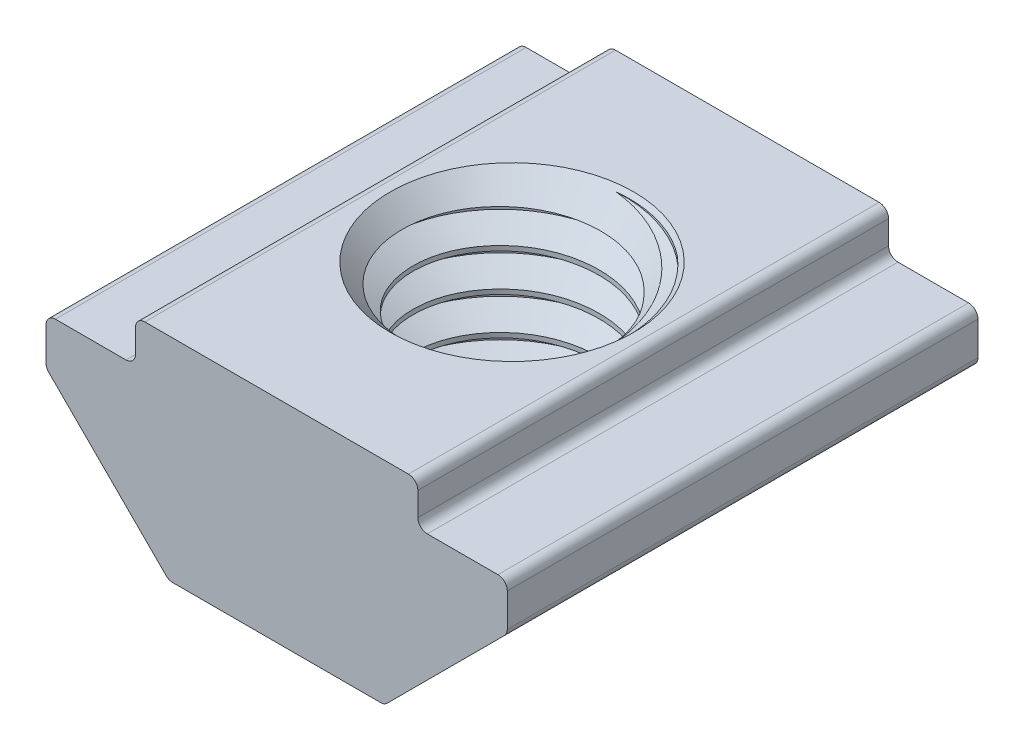
SolidWorks part; units mm, degrees
ref_plane "Front Plane" through (0, 0, 0) normal (0, 0, 1) x (1, 0, 0)
ref_plane "Top Plane" through (0, 0, 0) normal (0, 1, 0) x (1, 0, 0)
ref_plane "Right Plane" through (0, 0, 0) normal (1, 0, 0) x (0, 0, -1)
sketch "Sketch1" plane through (0, 0, 0) normal (1, 0, 0) x (0, 0, -1)
  line L0 (0, 2.25) -> (0, -2.25) construction
  line L1 (-5, -2.25) -> (5, -2.25) construction
  line L2 (-2.5, 2.25) -> (2.5, 2.25) construction
  line L3 (2.5866, 3) -> (1.8938, 2.6) construction
  line L4 (1.8938, 2.6) -> (2.5866, 2.2) construction
  line L5 (2.5866, 2.2) -> (2.5866, 3) construction
  line L6 (2.5, 2.95) -> (2.5, 2.25) construction
  line L7 (2.5866, 2.6) -> (2.5, 2.6) construction
  line L8 (2.5, 2.6) -> (1.9804, 2.6) construction
  line L9 (1.9804, 2.6) -> (1.8938, 2.6) construction
  line L10 (1.9804, 2.65) -> (1.9804, 2.55)
  line L11 (2.5433, 2.975) -> (2.5433, 2.225)
  line L12 (1.9804, 2.55) -> (2.5433, 2.225)
  line L13 (1.9804, 2.65) -> (2.5433, 2.975)
  point P3 (0, 1.35)
  point P20 (2.5433, 2.6)
  dimension "Nut Height" = 4.5
  dimension "Nut Step Height" = 0.9
  dimension "Nut Length" = 10
  dimension "Thread Size" = 5
  dimension "Thread Pitch" = 0.8
  dimension "D2" = 0.1
sketch "Sketch2" plane through (0, 0, 0) normal (0, 0, 1) x (1, 0, 0)
  line L0 (-4.9, 1.35) -> (4.9, 1.35) construction
  line L1 (-3, 2.25) -> (3, 2.25) construction
  dimension "Nut Width" = 9.8
  dimension "Nut Step Width" = 6
sketch "Sketch3" plane through (0, 0, 0) normal (0, 0, 1) x (1, 0, 0)
  line L0 (-4.9, 1.35) -> (-3, 1.35)
  line L1 (-4.9, 1.35) -> (4.9, 1.35) construction
  line L2 (-3, 1.35) -> (-3, 2.25)
  line L3 (-3, 2.25) -> (3, 2.25)
  line L4 (0, 2.25) -> (0, -2.25) construction
  line L5 (2.29, -2.25) -> (-2.29, -2.25)
  line L6 (-2.29, -2.25) -> (-4.9, 0.36)
  line L7 (-4.9, 0.36) -> (-4.9, 1.35)
  line L8 (4.9, 0.36) -> (4.9, 1.35)
  line L9 (2.29, -2.25) -> (4.9, 0.36)
  line L10 (3, 1.35) -> (3, 2.25)
  line L11 (4.9, 1.35) -> (3, 1.35)
  dimension "D1" = 135
  dimension "D2" = 0.99
extrude "Boss-Extrude1" add sketch "Sketch3" against normal up to vertex (5 mm away) from vertex at 5 starting at point (0, -2.25, 5)
sketch "Sketch12" plane through (0, 2.25, 0) normal (0, 1, 0) x (1, 0, 0)
  line L0 (0, 1.9804) -> (0, 2.5433) construction
  circle A0 centre (0, 0) radius 2.5
  circle A1 centre (0, 0) radius 2.2618
  point P3 (0, 2.2618)
  point P5 (2.2618, 0)
fillet "Fillet1" radius 0.2 10 edges at (-4.9, 0.36, 0) (-2.29, -2.25, 0) (2.29, -2.25, 0) (4.9, 0.36, 0) (4.9, 1.35, 0) (3, 1.35, 0) (-3, 2.25, 0) (-3, 1.35, 0) (-4.9, 1.35, 0) (3, 2.25, 0)
sketch "Sketch4" plane through (0, 2.25, 0) normal (0, 1, 0) x (1, 0, 0)
  circle A0 centre (0, 0) radius 2.5
extrude "Cut-Extrude1" cut sketch "Sketch4" against normal through all
sketch "Sketch5" plane through (0, 2.25, 0) normal (0, 1, 0) x (1, 0, 0)
  line L0 (-3, 0) -> (3, 0) construction
  circle A0 centre (0, 0) radius 2.5866
extrude "Cut-Extrude2" cut sketch "Sketch5" against normal blind 2.54 draft 45
sketch "Sketch11" plane through (0, -2.25, 0) normal (0, -1, 0) x (1, 0, 0)
  circle A1 centre (0, 0) radius 2.5866
  circle A2 centre (0, 0) radius 2.5866
  dimension "D1" = 0
extrude "Cut-Extrude6" cut sketch "Sketch11" along normal blind 2.54 draft 45 from offset 0.2667
sketch "Sketch6" plane through (0, 2.25, 0) normal (0, 1, 0) x (1, 0, 0)
  circle A0 centre (0, 0) radius 2.5 construction
  circle A1 centre (0, 0) radius 2.5
curve "Helix/Spiral1" pitch 0.8 height 5.4 turns 6.75
sketch "Sketch7" plane through (0, 0, 0) normal (1, 0, 0) x (0, 0, -1)
  line L0 (1.9804, 2.65) -> (1.9804, 2.55) construction
  line L1 (1.9804, 2.55) -> (2.5433, 2.225) construction
  line L2 (2.5433, 2.975) -> (2.5433, 2.225) construction
  line L3 (1.9804, 2.65) -> (2.5433, 2.975) construction
  line L4 (1.9804, 2.65) -> (1.9804, 2.55)
  line L5 (1.9804, 2.55) -> (2.5433, 2.225)
  line L6 (2.5433, 2.975) -> (2.5433, 2.225)
  line L7 (1.9804, 2.65) -> (2.5433, 2.975)
sweep "Sweep1" add profiles "Sketch7" path "Helix/Spiral1"
sketch "Sketch8" plane through (0, 2.25, 0) normal (0, 1, 0) x (1, 0, 0)
  circle A0 centre (0, 0) radius 2.5866 construction
  circle A2 centre (0, 0) radius 2.5866
extrude "Cut-Extrude3" cut sketch "Sketch8" against normal through all draft 45 and the other way through all
sketch "Sketch9" plane through (0, -2.25, 0) normal (0, -1, 0) x (1, 0, 0)
  arc A1 (-2.2072, -1.8082) -> (2.2072, -1.8082) centre (0, 0) ccw construction
  circle A2 centre (0, 0) radius 2.8533
extrude "Cut-Extrude4" cut sketch "Sketch9" against normal through all draft 45 and the other way through all
equation "\"D2@Sketch1\" = \"Thread Pitch@Sketch1\" / 8"
equation "\"D2@Sketch3\" = \"Nut Step Height@Sketch1\" * 1.1"
equation "\"D4@Helix/Spiral1\"=\"Thread Pitch@Sketch1\""
equation "\"D3@Helix/Spiral1\" = \"Nut Height@Sketch1\" + \"Nut Step Height@Sketch1\""
equation "\"D19@Cut-Extrude6\"=\"Thread Pitch@Sketch1\"/3"
